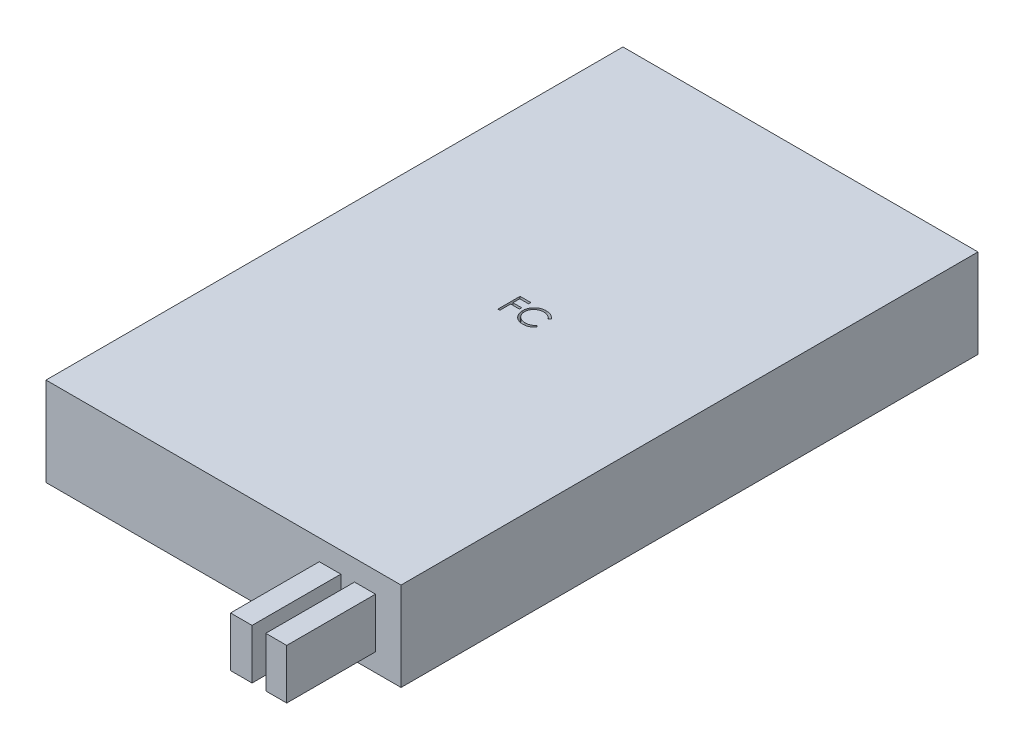
SolidWorks part; units mm, degrees
ref_plane "Front Plane" through (0, 0, 0) normal (0, 0, 1) x (1, 0, 0)
ref_plane "Top Plane" through (0, 0, 0) normal (0, 1, 0) x (1, 0, 0)
ref_plane "Right Plane" through (0, 0, 0) normal (1, 0, 0) x (0, 0, -1)
sketch "Sketch1" plane through (0, 0, 0) normal (0, 1, 0) x (1, 0, 0)
  line L1 (-25.4, -41.275) -> (25.4, -41.275)
  line L2 (-25.4, -41.275) -> (-25.4, 41.275)
  line L3 (-25.4, 41.275) -> (25.4, 41.275)
  line L4 (25.4, -41.275) -> (25.4, 41.275)
  line L5 (-25.4, -41.275) -> (25.4, 41.275) construction
  line L6 (-25.4, 41.275) -> (25.4, -41.275) construction
  point P0 (0, 0)
  dimension "D1" = 82.55
  dimension "D2" = 50.8
extrude "Boss-Extrude1" add sketch "Sketch1" along normal blind 12.7
sketch "Sketch2" plane through (0, 12.7, 0) normal (0, 1, 0) x (1, 0, 0)
  text T0 "FC"
extrude "Cut-Extrude1" cut sketch "Sketch2" against normal blind 1.27
sketch "Sketch3" plane through (0, 0, 41.275) normal (0, 0, 1) x (1, 0, 0)
  line L1 (18.745, 9.7414) -> (21.7439, 9.7414)
  line L2 (18.745, 9.7414) -> (18.745, 2.5959)
  line L3 (18.745, 2.5959) -> (21.7439, 2.5959)
  line L4 (21.7439, 9.7414) -> (21.7439, 2.5959)
  line L5 (13.7037, 9.7414) -> (16.7837, 9.7414)
  line L6 (13.7037, 9.7414) -> (13.7037, 2.5959)
  line L7 (13.7037, 2.5959) -> (16.7837, 2.5959)
  line L8 (16.7837, 9.7414) -> (16.7837, 2.5959)
extrude "Boss-Extrude2" add sketch "Sketch3" along normal blind 12.7
equation "\"D1@Sketch1\"=\"Flight Controller Y@Quad Assemb.sldasm\""
equation "\"D2@Sketch1\"=\"Flight Controller X@Quad Assemb.sldasm\""
equation "\"D1@Boss-Extrude1\"=\"Flight Controller Z@Quad Assemb.sldasm\""
